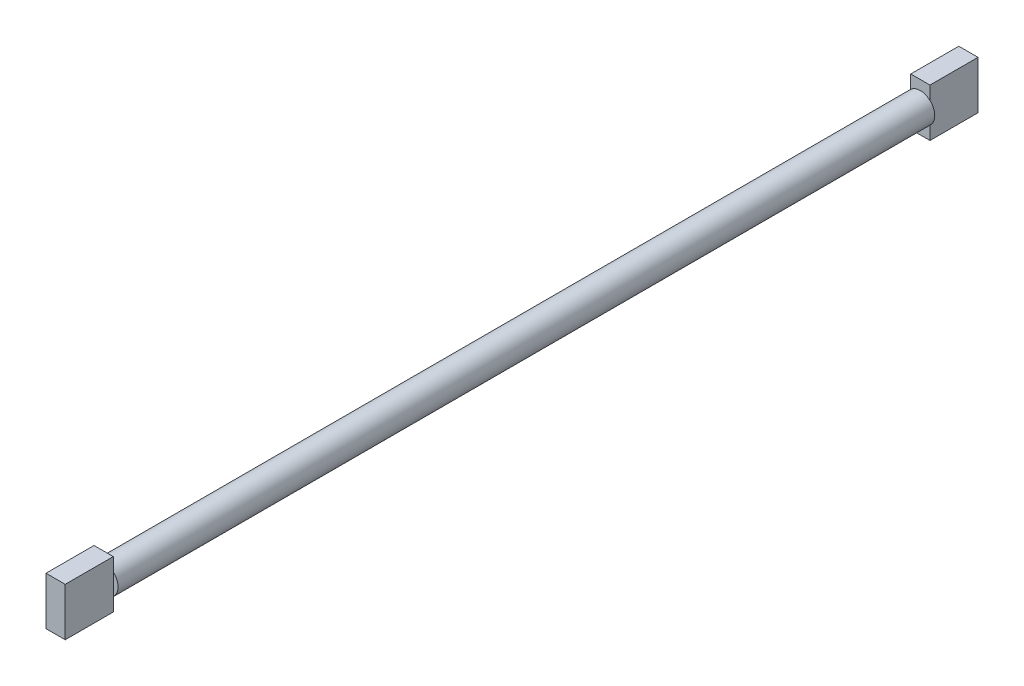
SolidWorks part; units mm, degrees
ref_plane "Front Plane" through (0, 0, 0) normal (0, 0, 1) x (1, 0, 0)
ref_plane "Top Plane" through (0, 0, 0) normal (0, 1, 0) x (1, 0, 0)
ref_plane "Right Plane" through (0, 0, 0) normal (1, 0, 0) x (0, 0, -1)
sketch "Sketch1" plane through (0, 0, 0) normal (0, 0, 1) x (1, 0, 0)
  circle A0 centre (0, 0) radius 15
extrude "Boss-Extrude1" add sketch "Sketch1" along normal blind 850
ref_plane "Plane1" through (0, 0, 425) normal (0, 0, -1) x (-1, 0, 0)
sketch "Sketch3" plane through (0, 0, 850) normal (0, 0, 1) x (1, 0, 0)
  line L1 (-10, 25) -> (10, 25)
  line L2 (-10, 25) -> (-10, -25)
  line L3 (-10, -25) -> (10, -25)
  line L4 (10, 25) -> (10, -25)
  line L5 (-10, 25) -> (10, -25) construction
  line L6 (-10, -25) -> (10, 25) construction
  point P0 (0, 0)
extrude "Boss-Extrude2" add sketch "Sketch3" along normal blind 50
mirror "Mirror1" about plane through (0, 0, 425) normal (0, 0, -1) of "Boss-Extrude2"
